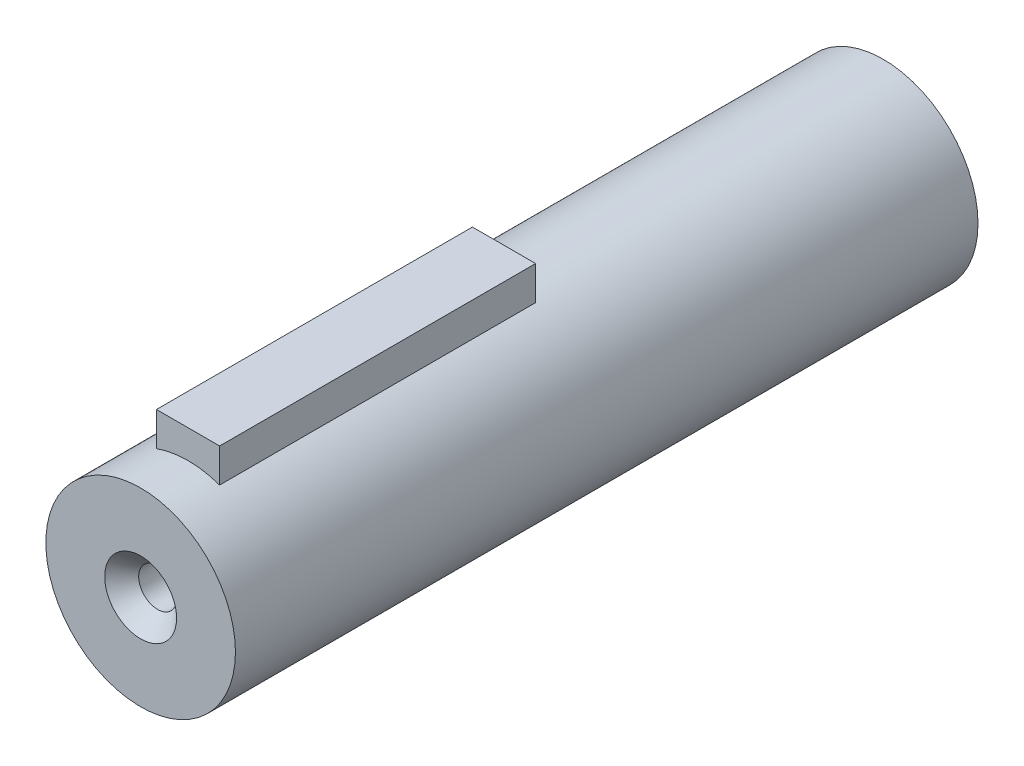
SolidWorks part; units mm, degrees
ref_plane "정면" through (0, 0, 0) normal (0, 0, 1) x (1, 0, 0)
ref_plane "윗면" through (0, 0, 0) normal (0, 1, 0) x (1, 0, 0)
ref_plane "우측면" through (0, 0, 0) normal (1, 0, 0) x (0, 0, -1)
sketch "스케치1" plane through (0, 0, 0) normal (0, 0, 1) x (1, 0, 0)
  circle A0 centre (0, 0) radius 6
  dimension "D1" = 12
extrude "보스-돌출1" add sketch "스케치1" along normal blind 47 contours A0
ref_plane "평면1" through (0, 6, 0) normal (0, 1, 0) x (0, 0, -1)
sketch "스케치2" plane through (0, 6, 0) normal (0, 1, 0) x (0, 0, -1)
  line L0 (-47, 6) -> (-47, -6) construction
  line L1 (-44, -2) -> (-24, -2)
  line L2 (-44, -2) -> (-44, 2)
  line L3 (-44, 2) -> (-24, 2)
  line L4 (-24, -2) -> (-24, 2)
  line L5 (-44, -2) -> (-24, 2) construction
  line L6 (-44, 2) -> (-24, -2) construction
  point P0 (-34, 0)
  point P8 (0, 0)
  dimension "D1" = 4
  dimension "D2" = 20
  dimension "D3" = 3
extrude "보스-돌출2" add sketch "스케치2" along normal blind 1.8 and the other way up to surface (1.8 mm away) contours L1 L4 L3 L2
hole_wizard "M2 여유 구멍2" positions "스케치5" profile "스케치6" hole size "M2" standard "KS"
sketch "스케치5" plane through (0, 0, 47) normal (0, 0, 1) x (1, 0, 0)
  point P0 (0, 0)
sketch "스케치6" plane through (0, 0, 47) normal (1, 0, 0) x (0, -1, 0)
  line L0 (0, 0) -> (0, 5.721)
  line L1 (0, 5.721) -> (1.2, 5)
  line L2 (1.2, 5) -> (1.2, 1.075)
  line L3 (1.2, 1.075) -> (2.275, 0)
  line L5 (2.275, 0) -> (0, 0)
  line L6 (-1.2, 1.075) -> (-2.275, 0) construction
  line L10 (0, 5.721) -> (-1.2, 5) construction
  line L11 (0, -6.35) -> (0, 107.95) construction
  dimension "구멍 지름" = 2.4
  dimension "구멍 깊이" = 5
  dimension "표면 카운터싱크 지름" = 4.55
  dimension "표면 카운터싱크 각도" = 90
  dimension "드릴 각도" = 118
hole_wizard "M2 여유 구멍3" positions "스케치7" profile "스케치8" hole size "M2" standard "KS"
sketch "스케치7" plane through (0, 0, 0) normal (0, 0, -1) x (-1, 0, 0)
  point P0 (0, 0)
sketch "스케치8" plane through (0, 0, 0) normal (1, 0, 0) x (0, 1, 0)
  line L0 (0, 0) -> (0, 5.721)
  line L1 (0, 5.721) -> (1.2, 5)
  line L2 (1.2, 5) -> (1.2, 1.075)
  line L3 (1.2, 1.075) -> (2.275, 0)
  line L5 (2.275, 0) -> (0, 0)
  line L6 (-1.2, 1.075) -> (-2.275, 0) construction
  line L10 (0, 5.721) -> (-1.2, 5) construction
  line L11 (0, -6.35) -> (0, 107.95) construction
  dimension "구멍 지름" = 2.4
  dimension "구멍 깊이" = 5
  dimension "표면 카운터싱크 지름" = 4.55
  dimension "표면 카운터싱크 각도" = 90
  dimension "드릴 각도" = 118
